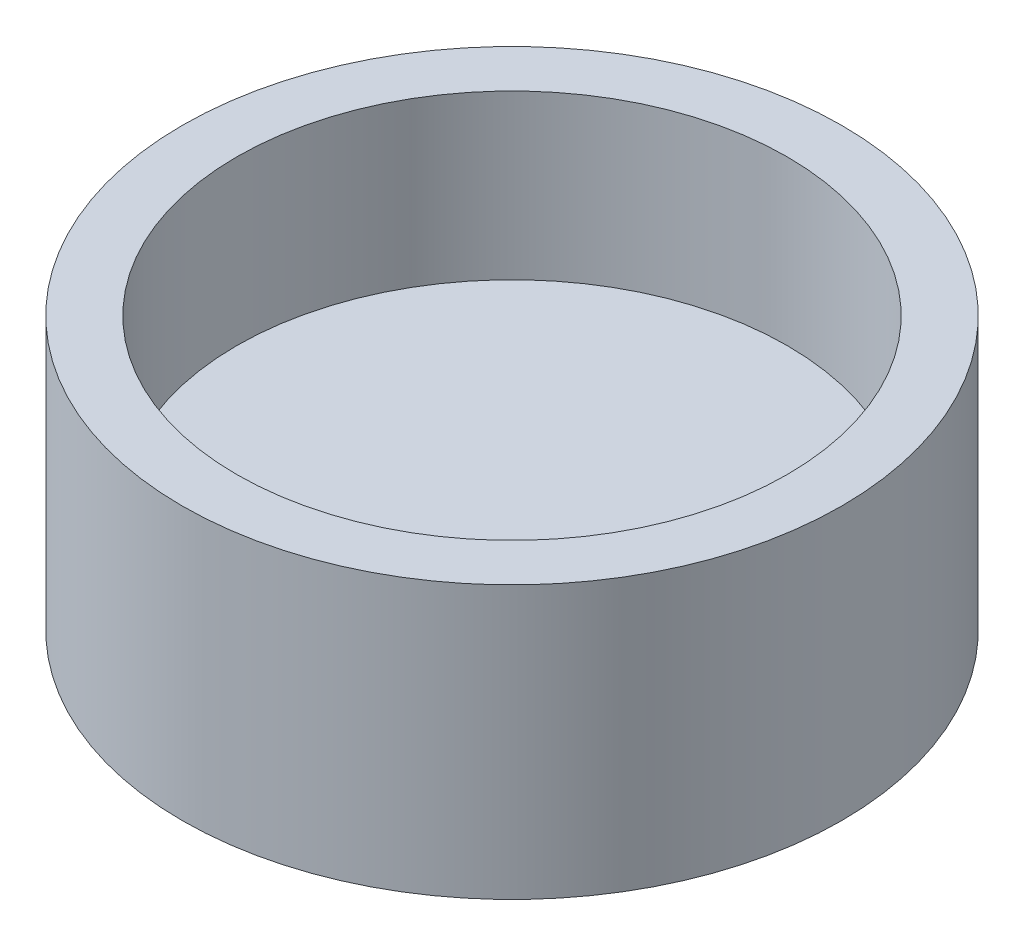
SolidWorks part; units mm, degrees
ref_plane "前视基准面" through (0, 0, 0) normal (0, 0, 1) x (1, 0, 0)
ref_plane "上视基准面" through (0, 0, 0) normal (0, 1, 0) x (1, 0, 0)
ref_plane "右视基准面" through (0, 0, 0) normal (1, 0, 0) x (0, 0, -1)
other "Configuration Table"
sketch "草图1" plane through (0, 0, 0) normal (0, 1, 0) x (1, 0, 0)
  circle A0 centre (0, 0) radius 6.05
  dimension "D1" = 12.1
extrude "凸台-拉伸1" add sketch "草图1" along normal blind 5
sketch "草图2" plane through (0, 5, 0) normal (0, 1, 0) x (1, 0, 0)
  circle A0 centre (0, 0) radius 5.05
  dimension "D1" = 10.1
extrude "切除-拉伸1" cut sketch "草图2" against normal blind 3
